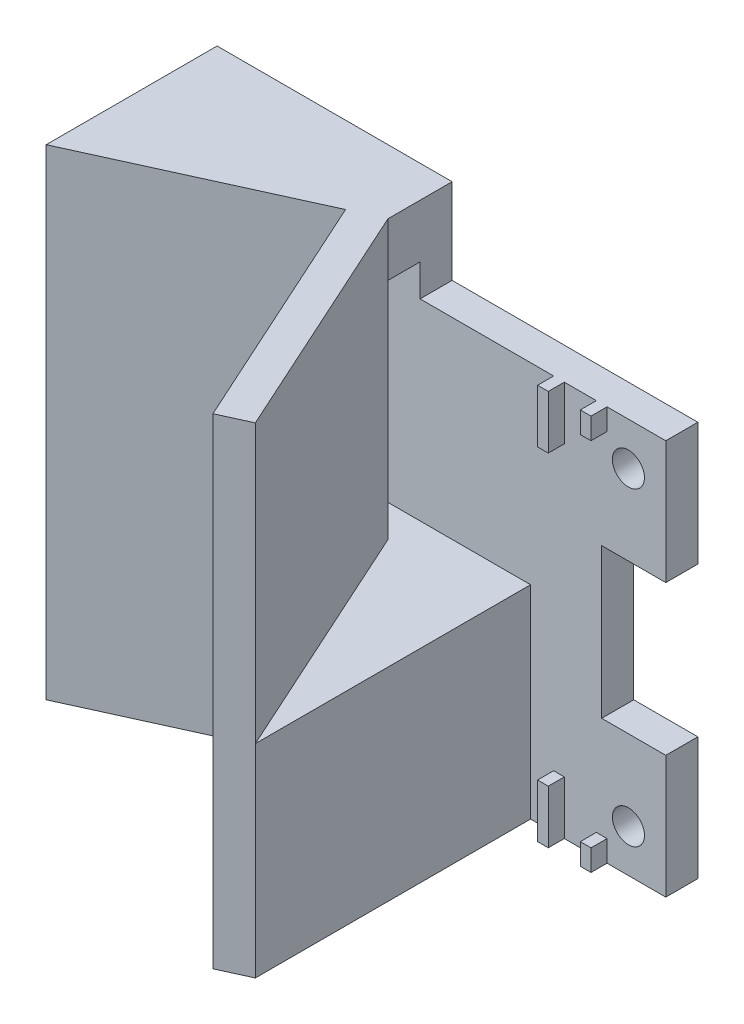
SolidWorks part; units mm, degrees
ref_plane "Alzado" through (0, 0, 0) normal (0, 0, 1) x (1, 0, 0)
ref_plane "Planta" through (0, 0, 0) normal (0, 1, 0) x (1, 0, 0)
ref_plane "Vista lateral" through (0, 0, 0) normal (1, 0, 0) x (0, 0, -1)
sketch "Croquis1" plane through (0, 0, 0) normal (0, 0, 1) x (1, 0, 0)
  line L1 (-52.1973, 33.4619) -> (-4.1973, 33.4619)
  line L2 (-56.1973, 29.4619) -> (-56.1973, 0.4619)
  line L3 (-52.4067, -3.5381) -> (-4.1973, -3.5381)
  line L4 (-4.1973, 33.4619) -> (-4.1973, -3.5381)
  line L5 (-56.1973, 24.9619) -> (-49.1973, 24.9619)
  line L6 (-56.1973, 24.9619) -> (-56.1973, 4.9619)
  line L7 (-56.1973, 4.9619) -> (-49.1973, 4.9619)
  line L8 (-49.1973, 24.9619) -> (-49.1973, 4.9619)
  line L9 (-4.1973, 21.9619) -> (-10.1973, 21.9619)
  line L10 (-4.1973, 21.9619) -> (-4.1973, 7.9619)
  line L11 (-4.1973, 7.9619) -> (-10.1973, 7.9619)
  line L12 (-10.1973, 21.9619) -> (-10.1973, 7.9619)
  circle A0 centre (-52.1973, 29.4619) radius 1.5
  circle A1 centre (-7.6973, 29.4619) radius 1.5
  circle A2 centre (-52.1915, 0.4619) radius 1.5
  circle A3 centre (-7.6915, 0.4619) radius 1.5
  arc A4 (-56.1973, 29.4619) -> (-52.1973, 33.4619) centre (-52.1973, 29.4619) cw
  arc A5 (-52.4067, -3.5381) -> (-56.1973, 0.4619) centre (-52.1915, 0.4619) cw
  dimension "D3" = 4
  dimension "D5" = 44.5
  dimension "D6" = 4
  dimension "D7" = 29
  dimension "D1" = 8.5
  dimension "D2" = 20
  dimension "D4" = 4
  dimension "D8" = 4
  dimension "D9" = 44.5
  dimension "D10" = 7
  dimension "D11" = 11.5
  dimension "D12" = 6
  dimension "D13" = 14
  dimension "D14" = 48
extrude "Saliente-Extruir1" add sketch "Croquis1" along normal blind 3 contours A5 L3 L4 L11 L12 L9 L1 A4 L2 L5 L8 L7 A3 A2 A1 A0
sketch "Croquis3" plane through (0, 0, 3) normal (0, 0, 1) x (1, 0, 0)
  line L0 (-52.1973, 33.4619) -> (-4.1973, 33.4619) construction
  line L1 (-49.1973, 33.4619) -> (-27.1973, 33.4619)
  line L2 (-49.1973, 33.4619) -> (-49.1973, -3.5381)
  line L3 (-49.1973, -3.5381) -> (-27.1973, -3.5381)
  line L4 (-27.1973, 33.4619) -> (-27.1973, -3.5381)
  line L5 (-52.4067, -3.5381) -> (-4.1973, -3.5381) construction
  circle A0 centre (-52.1973, 29.4619) radius 1.5 construction
  dimension "D1" = 3
  dimension "D2" = 22
extrude "Saliente-Extruir2" add sketch "Croquis3" along normal blind 13
sketch "Croquis4" plane through (0, -3.5381, 0) normal (0, -1, 0) x (1, 0, 0)
  line L0 (-27.1973, 16) -> (-27.1973, 6.0021)
  line L1 (-27.1973, 16) -> (-27.1973, 3) construction
  line L2 (-27.1973, 16) -> (-49.1973, 16)
  line L7 (-27.1973, 6.0021) -> (-49.1973, 16)
  line L8 (-27.1973, 3) -> (-4.1973, 3) construction
  dimension "D1" = 3.0021
extrude "Cortar-Extruir1" cut sketch "Croquis4" against normal up to vertex
sketch "Croquis6" plane through (0, 33.4619, 0) normal (0, 1, 0) x (1, 0, 0)
  line L0 (-27.1973, -6.0021) -> (-49.1973, -16)
  line L1 (-49.1973, -16) -> (-49.1973, 0)
  line L2 (-52.1973, 0) -> (-4.1973, 0) construction
  line L3 (-49.1973, 0) -> (-27.1973, 0)
  line L4 (-27.1973, 0) -> (-27.1973, -6.0021)
extrude "Saliente-Extruir4" add sketch "Croquis6" along normal blind 8
sketch "Croquis7" plane through (-27.1973, 0, 0) normal (1, 0, 0) x (0, 0, -1)
  line L0 (-6.0021, 41.4619) -> (-6.0021, -3.5381) construction
  line L1 (-6.0021, 15.4619) -> (-3, 15.4619)
  line L2 (-6.0021, 15.4619) -> (-6.0021, 36.4619)
  line L3 (-6.0021, 36.4619) -> (-3, 36.4619)
  line L4 (-3, 15.4619) -> (-3, 36.4619)
  line L5 (-6.0021, -3.5381) -> (-3, -3.5381) construction
  line L6 (-6.0021, 41.4619) -> (0, 41.4619) construction
  dimension "D1" = 19
  dimension "D2" = 5
extrude "Cortar-Extruir2" cut sketch "Croquis7" against normal up to vertex (22 mm away)
sketch "Croquis8" plane through (-2.3947, 0, -5.2695) normal (0.4137, 0, 0.9104) x (0.9104, 0, -0.4137)
  line L0 (-51.4089, 41.4619) -> (-27.2436, 41.4619) construction
  line L1 (-27.2436, -3.5381) -> (-30.2436, -3.5381)
  line L2 (-27.2436, -3.5381) -> (-27.2436, 41.4619)
  line L3 (-27.2436, 41.4619) -> (-30.2436, 41.4619)
  line L4 (-30.2436, -3.5381) -> (-30.2436, 41.4619)
  dimension "D1" = 3
extrude "Saliente-Extruir5" add sketch "Croquis8" along normal blind 25
sketch "Croquis9" plane through (0, -3.5381, 0) normal (0, -1, 0) x (1, 0, 0)
  line L0 (-16.854, 28.762) -> (-27.1973, 6.0021)
  line L1 (-27.1973, 6.0021) -> (-27.1973, 3)
  line L2 (-27.1973, 3) -> (-16.854, 3)
  line L3 (-27.1973, 3) -> (-4.1973, 3) construction
  line L4 (-16.854, 3) -> (-16.854, 28.762)
extrude "Saliente-Extruir6" add sketch "Croquis9" against normal up to vertex
sketch "Croquis13" plane through (0, 0, 3) normal (0, 0, 1) x (1, 0, 0)
  line L0 (-16.854, -3.5381) -> (-4.1973, -3.5381) construction
  line L1 (-10.6973, -3.5381) -> (-9.6973, -3.5381)
  line L2 (-10.6973, -3.5381) -> (-10.6973, -1.5381)
  line L3 (-10.6973, -1.5381) -> (-9.6973, -1.5381)
  line L4 (-9.6973, -3.5381) -> (-9.6973, -1.5381)
  line L5 (-4.1973, 7.9619) -> (-4.1973, -3.5381) construction
  line L6 (-10.6973, 31.4619) -> (-9.6973, 31.4619)
  line L7 (-10.6973, 31.4619) -> (-10.6973, 33.4619)
  line L8 (-10.6973, 33.4619) -> (-9.6973, 33.4619)
  line L9 (-9.6973, 31.4619) -> (-9.6973, 33.4619)
  line L10 (-13.6973, 28.4619) -> (-14.6973, 28.4619)
  line L11 (-13.6973, -3.5381) -> (-14.6973, -3.5381)
  line L12 (-13.6973, -3.5381) -> (-13.6973, 1.4619)
  line L13 (-13.6973, 1.4619) -> (-14.6973, 1.4619)
  line L14 (-14.6973, -3.5381) -> (-14.6973, 1.4619)
  line L15 (-13.6973, 28.4619) -> (-13.6973, 33.4619)
  line L16 (-13.6973, 33.4619) -> (-14.6973, 33.4619)
  line L17 (-14.6973, 28.4619) -> (-14.6973, 33.4619)
  dimension "D1" = 5.5
  dimension "D2" = 1
  dimension "D3" = 2
  dimension "D5" = 5
  dimension "D6" = 1
  dimension "D7" = 3
  dimension "D4" = 2
  dimension "D8" = 2
extrude "Saliente-Extruir8" add sketch "Croquis13" along normal blind 1.5
